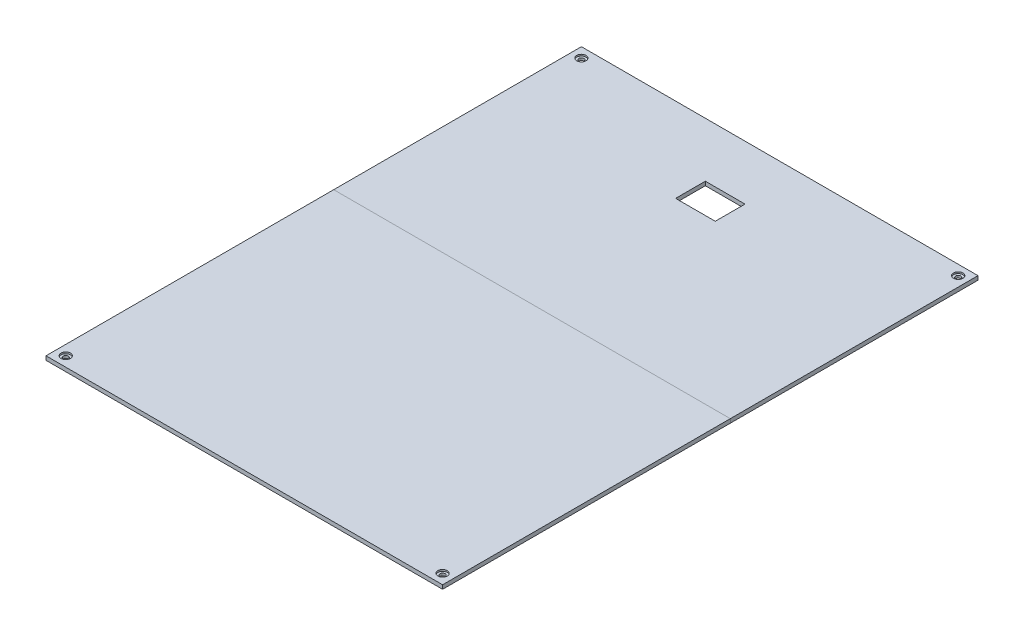
SolidWorks part; units mm, degrees
material "PLA"
ref_plane "Спереди" through (0, 0, 0) normal (0, 0, 1) x (1, 0, 0)
ref_plane "Сверху" through (0, 0, 0) normal (0, 1, 0) x (1, 0, 0)
ref_plane "Справа" through (0, 0, 0) normal (1, 0, 0) x (0, 0, -1)
sketch "Эскиз1" plane through (0, 0, 0) normal (0, 1, 0) x (1, 0, 0)
  line L1 (100, 135) -> (-100, 135)
  line L2 (100, 135) -> (100, -135)
  line L3 (100, -135) -> (-100, -135)
  line L4 (-100, 135) -> (-100, -135)
  line L5 (100, 135) -> (-100, -135) construction
  line L6 (100, -135) -> (-100, 135) construction
  point P0 (0, 0)
  dimension "D1" = 200
  dimension "D2" = 270
extrude "Бобышка-Вытянуть1" add sketch "Эскиз1" along normal blind 2
sketch "Эскиз2" plane through (0, 2, 0) normal (0, 1, 0) x (1, 0, 0)
  line L0 (0, 0) -> (0, 50000) construction
  line L1 (0, 0) -> (-50000, 0) construction
  line L2 (-100, 135) -> (-100, -135) construction
  line L3 (100, 135) -> (-100, 135) construction
  circle A0 centre (-95.0102, 130.0102) radius 1.3
  circle A1 centre (95.0102, 130.0102) radius 1.3
  circle A2 centre (95.0102, -130.0102) radius 1.3
  circle A3 centre (-95.0102, -130.0102) radius 1.3
  dimension "D1" = 2.6
  dimension "D2" = 4.9898
  dimension "D3" = 4.9898
extrude "Вырез-Вытянуть1" cut sketch "Эскиз2" against normal through all
sketch "Эскиз3" plane through (0, 2, 0) normal (0, 1, 0) x (1, 0, 0)
  circle A0 centre (-95.0102, 130.0102) radius 2.375
  circle A1 centre (95.0102, 130.0102) radius 2.375
  circle A2 centre (-95.0102, -130.0102) radius 2.375
  circle A3 centre (95.0102, -130.0102) radius 2.375
  dimension "D1" = 4.75
extrude "Вырез-Вытянуть2" cut sketch "Эскиз3" against normal blind 0.8
sketch "Эскиз4" plane through (0, 2, 0) normal (0, 1, 0) x (1, 0, 0)
  line L0 (0, 0) -> (0, 50000) construction
  line L1 (10, 107.5) -> (-10, 107.5)
  line L2 (10, 107.5) -> (10, 92.5)
  line L3 (10, 92.5) -> (-10, 92.5)
  line L4 (-10, 107.5) -> (-10, 92.5)
  line L5 (10, 107.5) -> (-10, 92.5) construction
  line L6 (10, 92.5) -> (-10, 107.5) construction
  line L7 (100, 135) -> (-100, 135) construction
  point P0 (0, 100)
  dimension "D1" = 20
  dimension "D2" = 15
  dimension "D3" = 35
extrude "Вырез-Вытянуть3" cut sketch "Эскиз4" against normal through all
sketch "Эскиз5" plane through (0, 0, 0) normal (0, -1, 0) x (1, 0, 0)
  line L0 (100, -135) -> (-100, -135) construction
  line L1 (100, 135) -> (100, -135) construction
  circle A0 centre (-3.9, -120.15) radius 1.75
  circle A1 centre (6.25, -88.45) radius 1.75
  circle A2 centre (-3.9, -120.15) radius 2.75
  circle A3 centre (6.25, -88.45) radius 2.75
  dimension "D1" = 3.5
  dimension "D2" = 14.85
  dimension "D3" = 103.9
  dimension "D4" = 10.15
  dimension "D5" = 31.7
  dimension "D6" = 1
extrude "Бобышка-Вытянуть2" add sketch "Эскиз5" along normal blind 2.7
ref_plane "Плоскость1" through (0, 0, -10.0835) normal (0, 0, -1) x (-1, 0, 0)
split "Разделить1" trim tools "Плоскость1" bodies to split 107 resulting bodies 108 109
